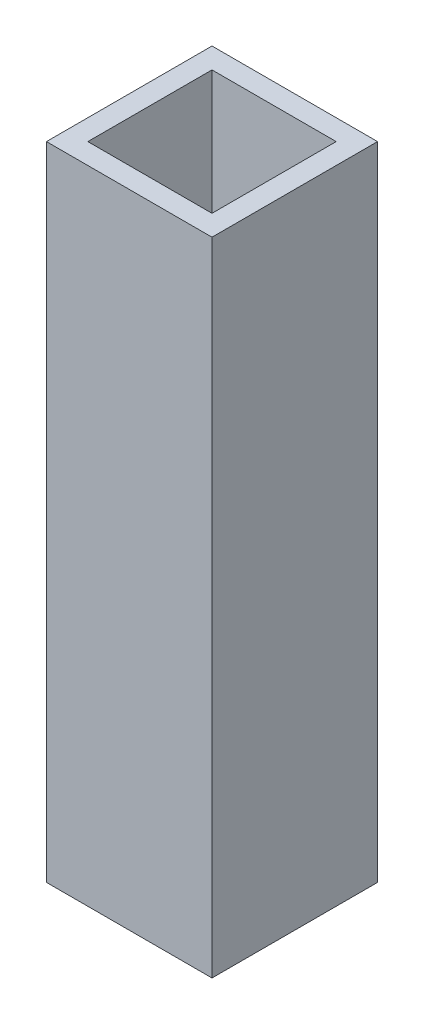
SolidWorks part; units mm, degrees
ref_plane "Front Plane" through (0, 0, 0) normal (0, 0, 1) x (1, 0, 0)
ref_plane "Top Plane" through (0, 0, 0) normal (0, 1, 0) x (1, 0, 0)
ref_plane "Right Plane" through (0, 0, 0) normal (1, 0, 0) x (0, 0, -1)
sketch "Sketch1" plane through (0, 0, 0) normal (0, 1, 0) x (1, 0, 0)
  line L1 (0, 0) -> (25.4, 0)
  line L2 (0, 0) -> (0, 25.4)
  line L3 (0, 25.4) -> (25.4, 25.4)
  line L4 (25.4, 0) -> (25.4, 25.4)
  line L5 (3.175, 3.175) -> (22.225, 3.175)
  line L6 (3.175, 3.175) -> (3.175, 22.225)
  line L7 (3.175, 22.225) -> (22.225, 22.225)
  line L8 (22.225, 3.175) -> (22.225, 22.225)
  dimension "D1" = 25.4
  dimension "D2" = 3.175
  dimension "D3" = 3.175
  dimension "D4" = 3.175
  dimension "D5" = 3.175
  dimension "D6" = 25.4
extrude "Boss-Extrude1" add sketch "Sketch1" along normal blind 98.425
